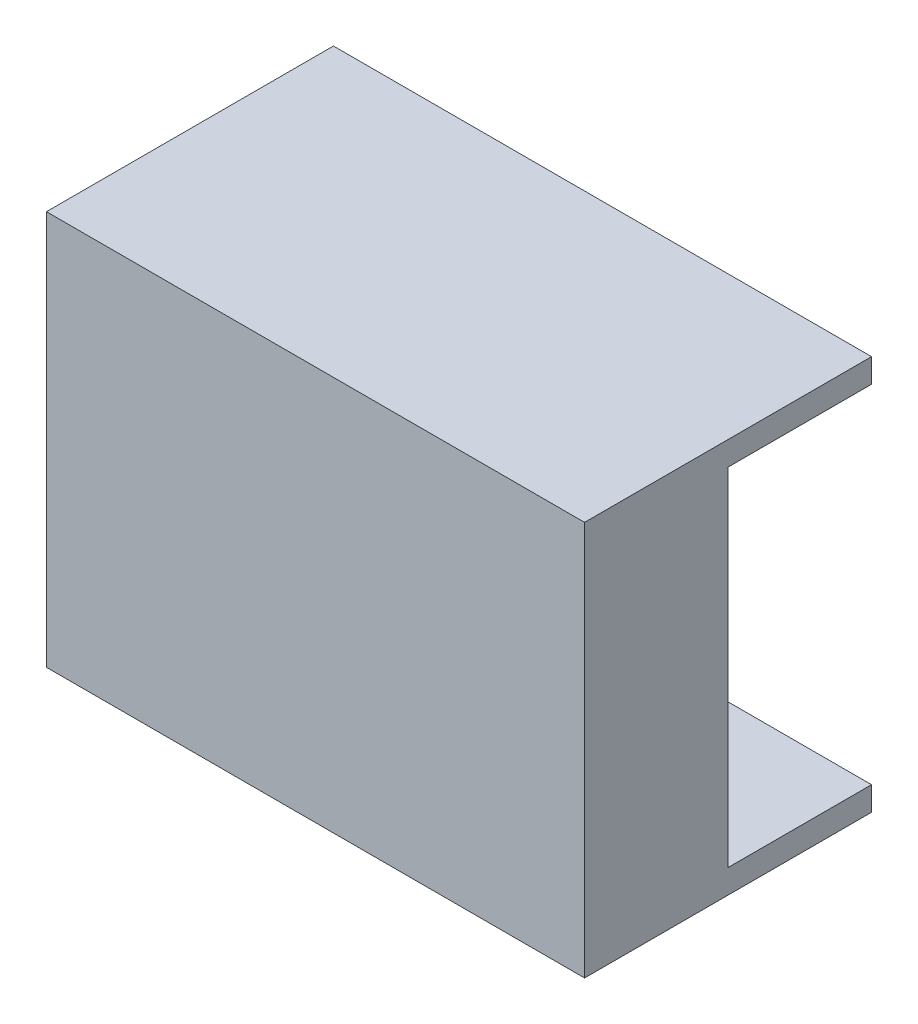
SolidWorks part; units mm, degrees
ref_plane "前视基准面" through (0, 0, 0) normal (0, 0, 1) x (1, 0, 0)
ref_plane "上视基准面" through (0, 0, 0) normal (0, 1, 0) x (1, 0, 0)
ref_plane "右视基准面" through (0, 0, 0) normal (1, 0, 0) x (0, 0, -1)
other "Configuration Table"
sketch "草图1" plane through (0, 0, 0) normal (0, 0, 1) x (1, 0, 0)
  line L0 (-45, 29) -> (45, 29)
  line L1 (45, 29) -> (45, 33)
  line L2 (45, 33) -> (-45, 33)
  line L3 (-45, 33) -> (-45, 29)
extrude "凸台-拉伸1" add sketch "草图1" along normal blind 24
sketch "草图2" plane through (0, 0, 0) normal (0, 0, 1) x (1, 0, 0)
  line L0 (-45, -33) -> (45, -33)
  line L1 (45, -33) -> (45, -29)
  line L2 (45, -29) -> (-45, -29)
  line L3 (-45, -29) -> (-45, -33)
extrude "凸台-拉伸2" add sketch "草图2" along normal blind 24
sketch "草图3" plane through (0, 0, 24) normal (0, 0, 1) x (1, 0, 0)
  line L0 (-45, -33) -> (45, -33)
  line L1 (45, -33) -> (45, 33)
  line L2 (45, 33) -> (-45, 33)
  line L3 (-45, 33) -> (-45, -33)
extrude "凸台-拉伸3" add sketch "草图3" along normal blind 24
